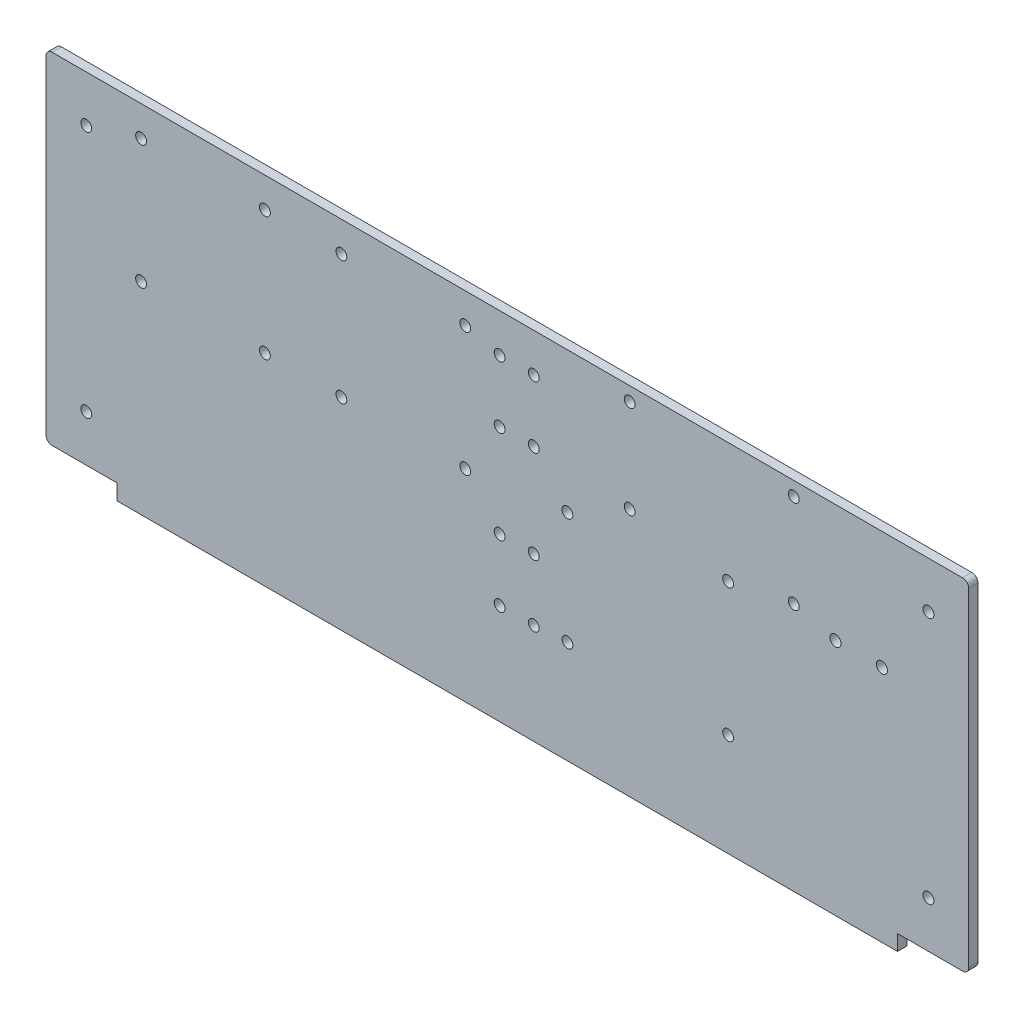
SolidWorks part; units mm, degrees
ref_plane "Front Plane" through (0, 0, 0) normal (0, 0, 1) x (1, 0, 0)
ref_plane "Top Plane" through (0, 0, 0) normal (0, 1, 0) x (1, 0, 0)
ref_plane "Right Plane" through (0, 0, 0) normal (1, 0, 0) x (0, 0, -1)
sketch "Sketch1" plane through (0, 0, 0) normal (0, 0, 1) x (1, 0, 0)
  line L6 (0, 219) -> (0, 204.5602) construction
  line L9 (-1068.2646, 219) -> (-57, 219) construction
  line L10 (126, 219) -> (126, 224)
  line L11 (126, 224) -> (147, 224)
  line L12 (149, 226) -> (149, 332)
  line L13 (147, 334) -> (-147, 334)
  line L14 (60, 219) -> (78.0401, 219) construction
  line L16 (-149, 226) -> (-149, 332)
  line L17 (-126, 224) -> (-147, 224)
  line L18 (-126, 219) -> (-126, 224)
  line L19 (126, 219) -> (70, 219)
  line L20 (-126, 219) -> (-70, 219)
  line L21 (-70, 219) -> (70, 219)
  line L22 (50, 65.6274) -> (50, 72.8673) construction
  line L23 (136, 236.6922) -> (136, 240.3102) construction
  circle A8 centre (136, 239) radius 1.75
  circle A9 centre (136, 319) radius 1.75
  arc A10 (-149, 332) -> (-147, 334) centre (-147, 332) cw
  arc A11 (149, 332) -> (147, 334) centre (147, 332) ccw
  circle A14 centre (-136, 239) radius 1.75
  circle A15 centre (-136, 319) radius 1.75
  arc A16 (-149, 226) -> (-147, 224) centre (-147, 226) ccw
  arc A17 (147, 224) -> (149, 226) centre (147, 226) ccw
  circle A18 centre (-78.3, 324.25) radius 1.75
  circle A19 centre (-2.5, 321.5) radius 1.75
  circle A20 centre (-78.3, 284.25) radius 1.75
  circle A26 centre (-118.3, 324.25) radius 1.75
  circle A27 centre (-118.3, 284.25) radius 1.75
  circle A28 centre (-53.6, 324.25) radius 1.75
  circle A29 centre (-53.6, 284.25) radius 1.75
  circle A30 centre (-13.6, 324.25) radius 1.75
  circle A31 centre (-13.6, 284.25) radius 1.75
  circle A32 centre (71.3, 295.2) radius 1.75
  circle A33 centre (19.4, 288.5) radius 1.75
  circle A34 centre (19.4, 252.2) radius 1.75
  circle A35 centre (71.3, 252.2) radius 1.75
  circle A36 centre (39.5, 329.5) radius 1.75
  circle A37 centre (39.5, 299.5) radius 1.75
  circle A38 centre (92.5, 329.5) radius 1.75
  circle A40 centre (92.5, 299.5) radius 1.75
  circle A41 centre (8.54, 321.5) radius 1.75
  circle A42 centre (-2.5, 301.5) radius 1.75
  circle A43 centre (8.54, 301.5) radius 1.75
  circle A44 centre (-2.5, 271.5) radius 1.75
  circle A45 centre (8.54, 271.5) radius 1.75
  circle A46 centre (8.54, 251.5) radius 1.75
  circle A47 centre (-2.5, 251.5) radius 1.75
  circle A48 centre (105.9775, 295.9451) radius 1.8
  circle A49 centre (120.9775, 295.9451) radius 1.8
  point P17 (-60, 219)
  point P37 (0, 334)
  point P50 (-149, 334)
  point P53 (149, 334)
  point P64 (-149, 224)
  point P67 (149, 224)
  point P90 (0, 0)
  point P94 (114.1158, 287.7146)
  point P95 (120.9765, 295.8834)
  point P96 (120.8428, 294.382)
  point P98 (120.9775, 295.8987)
  dimension "D2" = 149
  dimension "D3" = 3.5
  dimension "D4" = 3.5
  dimension "D7" = 3.5
  dimension "D8" = 3.5
  dimension "D9" = 15
  dimension "D10" = 15
  dimension "D11" = 2
  dimension "D12" = 2
  dimension "D13" = 115
  dimension "D5" = 3.5
  dimension "D6" = 3.5
  dimension "D15" = 3.5
  dimension "D17" = 3.5
  dimension "D18" = 3.5
  dimension "D19" = 3.5
  dimension "D20" = 3.5
  dimension "D21" = 3.5
  dimension "D22" = 3.5
  dimension "D23" = 3.5
  dimension "D24" = 3.5
  dimension "D25" = 3.5
  dimension "D26" = 3.5
  dimension "D27" = 3.5
  dimension "D28" = 3.5
  dimension "D29" = 3.5
  dimension "D30" = 3.5
  dimension "D31" = 3.5
  dimension "D32" = 3.5
  dimension "D33" = 3.5
  dimension "D34" = 3.5
  dimension "D35" = 3.5
  dimension "D36" = 3.6
  dimension "D37" = 3.6
  dimension "D38" = 15
  dimension "D14" = 106
  dimension "D16" = 126
extrude "Boss-Extrude1" add sketch "Sketch1" along normal blind 3
